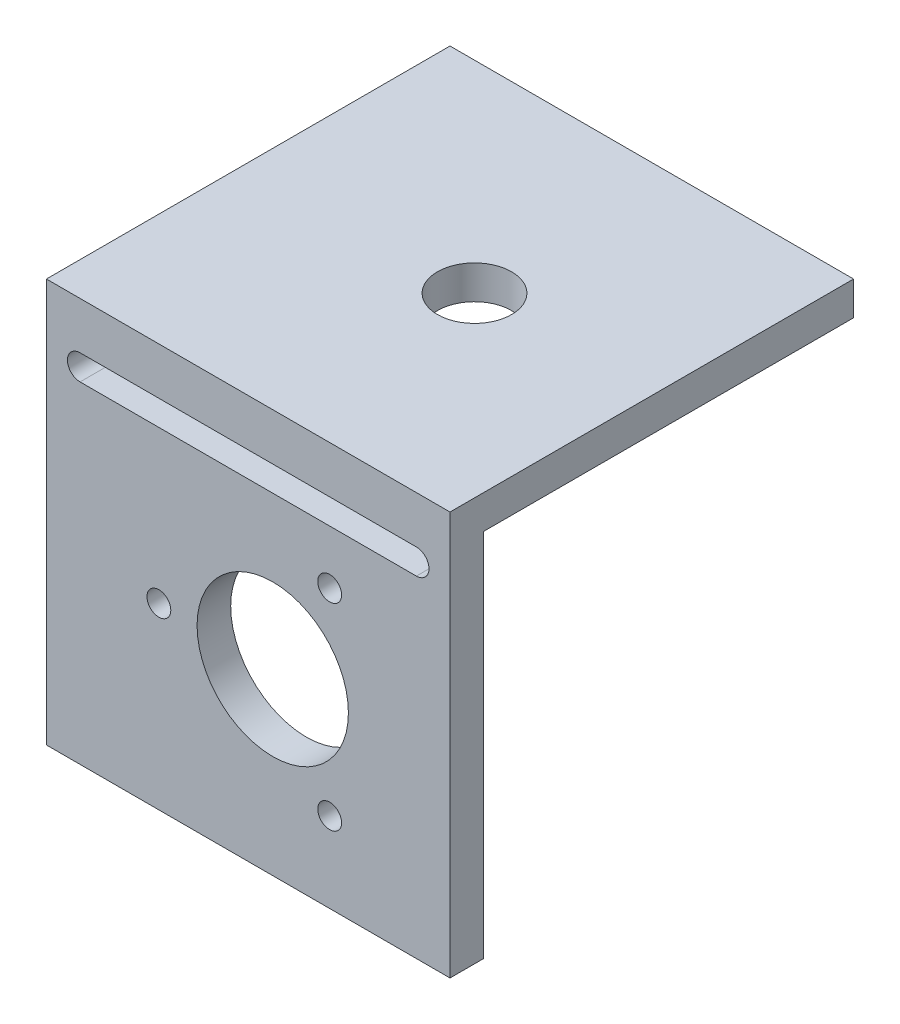
SolidWorks part; units mm, degrees
ref_plane "Front Plane" through (0, 0, 0) normal (0, 0, 1) x (1, 0, 0)
ref_plane "Top Plane" through (0, 0, 0) normal (0, 1, 0) x (1, 0, 0)
ref_plane "Right Plane" through (0, 0, 0) normal (1, 0, 0) x (0, 0, -1)
sketch "Sketch1" plane through (0, 0, 0) normal (1, 0, 0) x (0, 0, -1)
  line L0 (-6.35, 76.2) -> (69.85, 76.2)
  line L1 (69.85, 76.2) -> (69.85, 69.85)
  line L2 (69.85, 69.85) -> (0, 69.85)
  line L3 (0, 69.85) -> (0, 0)
  line L4 (0, 0) -> (-6.35, 0)
  line L5 (-6.35, 0) -> (-6.35, 76.2)
  line L6 (0, 38.4175) -> (0, -38.4175) construction
  line L7 (38.4175, 0) -> (-38.4175, 0) construction
  dimension "D1" = 6.35
  dimension "D2" = 6.35
  dimension "D3" = 76.2
  dimension "D4" = 76.2
extrude "Boss-Extrude1" add sketch "Sketch1" along normal blind 76.2
sketch "Sketch2" plane through (0, 0, 6.35) normal (0, 0, 1) x (1, 0, 0)
  circle A0 centre (42.7296, 33.762) radius 14.2875
  point P0 (42.7296, 33.762)
  dimension "D1" = 28.575
extrude "Cut-Extrude1" cut sketch "Sketch2" against normal through all contours A0
sketch "Sketch3" plane through (0, 0, 6.35) normal (0, 0, 1) x (1, 0, 0)
  point P0 (53.4796, 52.3815)
  point P1 (21.2296, 33.762)
  point P3 (53.4796, 15.1425)
hole_wizard "M4 Clearance Hole1" positions "Sketch4" profile "Sketch5" hole size "M4" standard "ANSI Metric" end condition through all
sketch "Sketch4" plane through (0, 0, 6.35) normal (0, 0, 1) x (1, 0, 0)
  point P0 (53.4796, 52.3815)
  point P3 (21.2296, 33.762)
  point P6 (53.4796, 15.1425)
sketch "Sketch5" plane through (53.4796, 52.3815, 6.35) normal (1, 0, 0) x (0, -1, 0)
  line L0 (0, 0) -> (0, 76.2)
  line L1 (0, 76.2) -> (2.25, 76.2)
  line L2 (2.25, 76.2) -> (2.25, 0)
  line L5 (2.25, 0) -> (0, 0)
  line L11 (0, -6.35) -> (0, 107.95) construction
  dimension "Thru Hole Dia." = 4.5
  dimension "Thru Hole Depth" = 76.2
sketch "Sketch6" plane through (0, 76.2, 0) normal (0, 1, 0) x (1, 0, 0)
  circle A0 centre (42.7296, 31.75) radius 7
  point P0 (42.7296, 31.75)
  dimension "D1" = 14
extrude "Cut-Extrude2" cut sketch "Sketch6" against normal up to next contours A0
sketch "Sketch7" plane through (0, 0, 0) normal (0, 0, -1) x (-1, 0, 0)
  line L0 (-69.85, 64.9288) -> (-6.35, 64.9287) construction
  line L1 (-69.85, 67.31) -> (-6.35, 67.31)
  line L2 (-69.85, 62.5475) -> (-6.35, 62.5475)
  line L3 (-76.2, 69.85) -> (0, 69.85) construction
  line L4 (0, 0) -> (0, 69.85) construction
  arc A0 (-69.85, 67.31) -> (-69.85, 62.5475) centre (-69.85, 64.9288) ccw
  arc A1 (-6.35, 62.5475) -> (-6.35, 67.31) centre (-6.35, 64.9287) ccw
  point P2 (-38.1, 64.9287)
  dimension "D1" = 4.7625
  dimension "D2" = 2.54
  dimension "D3" = 63.5
  dimension "D4" = 6.35
extrude "Cut-Extrude3" cut sketch "Sketch7" against normal through all
